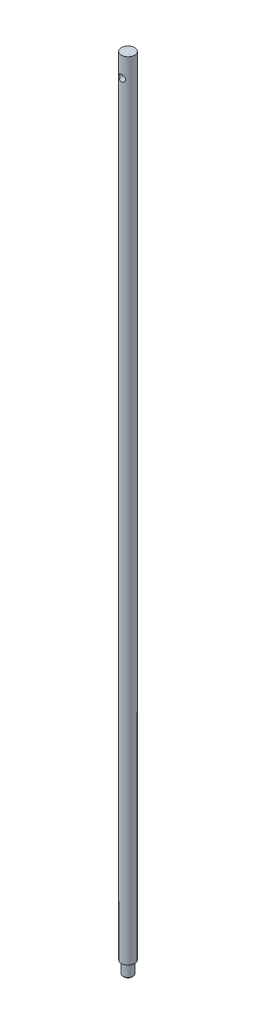
SolidWorks part; units mm, degrees
material "AISI 1020"
ref_plane "Front Plane" through (0, 0, 0) normal (0, 0, 1) x (1, 0, 0)
ref_plane "Top Plane" through (0, 0, 0) normal (0, 1, 0) x (1, 0, 0)
ref_plane "Right Plane" through (0, 0, 0) normal (1, 0, 0) x (0, 0, -1)
sketch "Sketch1" plane through (0, 0, 0) normal (0, 0, 1) x (1, 0, 0)
  line L0 (0, 0) -> (0, 768.35)
  line L1 (0, 768.35) -> (-6.35, 768.35)
  line L2 (-6.35, 768.35) -> (-6.35, 12.7)
  line L3 (-6.35, 12.7) -> (-4.7625, 12.7)
  line L4 (-4.7625, 12.7) -> (-4.7625, 0)
  line L5 (-4.7625, 0) -> (0, 0)
  dimension "D1" = 4.7625
  dimension "D2" = 6.35
  dimension "D3" = 768.35
  dimension "D4" = 12.7
revolve "Revolve1" add sketch "Sketch1" angle 360 about L0
chamfer "Chamfer1" distance 1.27 angle 45 1 edges at (0, 0, -4.7625)
sketch "Sketch2" plane through (0, 0, 0) normal (0, 0, 1) x (1, 0, 0)
  line L0 (6.35, 768.35) -> (-6.35, 768.35) construction
  circle A0 centre (0, 749.3) radius 3.175
  dimension "D2" = 6.35
  dimension "D1" = 19.05
extrude "Cut-Extrude1" cut sketch "Sketch2" against normal through all both and the other way through all
